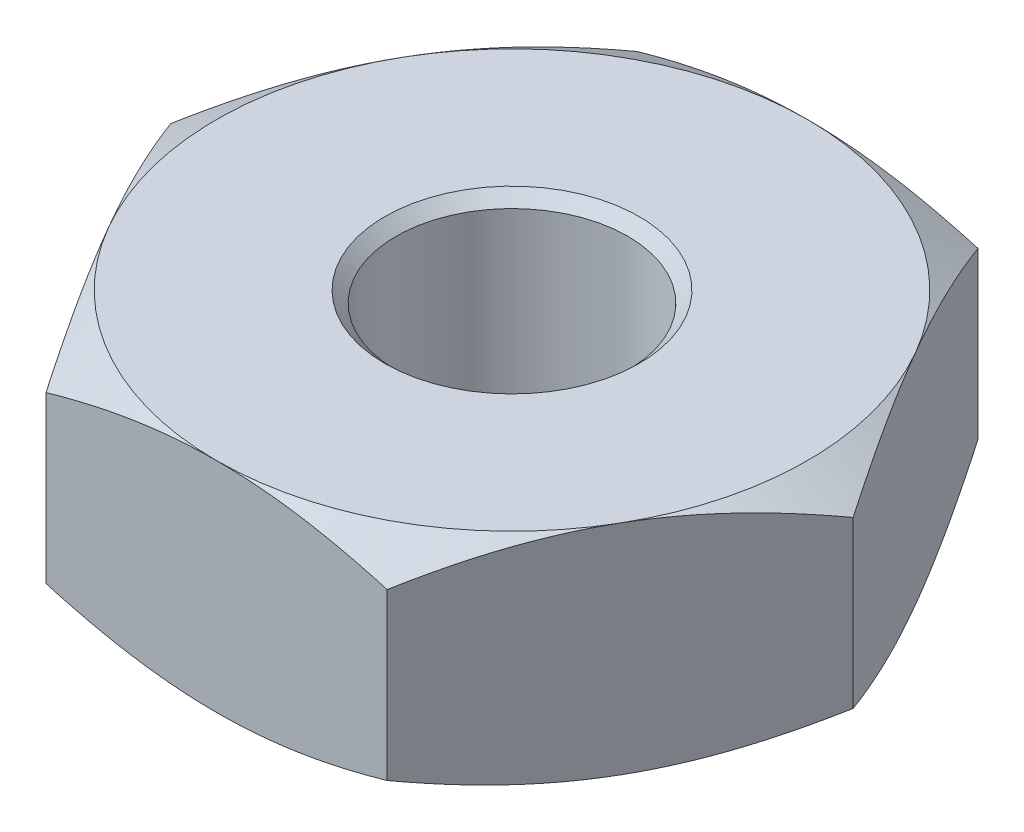
SolidWorks part; units mm, degrees
ref_plane "Front Plane" through (0, 0, 0) normal (0, 0, 1) x (1, 0, 0)
ref_plane "Top Plane" through (0, 0, 0) normal (0, 1, 0) x (1, 0, 0)
ref_plane "Right Plane" through (0, 0, 0) normal (1, 0, 0) x (0, 0, -1)
sketch "Sketch1" plane through (0, 0, 0) normal (0, 1, 0) x (1, 0, 0)
  line L1 (15.0111, 0) -> (7.5056, 13)
  line L2 (7.5056, 13) -> (-7.5056, 13)
  line L3 (-7.5056, 13) -> (-15.0111, 0)
  line L4 (-15.0111, 0) -> (-7.5056, -13)
  line L5 (-7.5056, -13) -> (7.5056, -13)
  line L6 (7.5056, -13) -> (15.0111, 0)
  circle A0 centre (0, 0) radius 13 construction
extrude "Boss-Extrude1" add sketch "Sketch1" along normal blind 9.6
sketch "Sketch2" plane through (0, 9.6, 0) normal (0, 1, 0) x (1, 0, 0)
  circle A0 centre (0, 0) radius 13
extrude "Cut-Extrude1" cut sketch "Sketch2" against normal blind 9.6 draft 60 flip side to cut
sketch "Sketch3" plane through (0, 0, 0) normal (0, -1, 0) x (1, 0, 0)
  circle A0 centre (0, 0) radius 13
extrude "Cut-Extrude2" cut sketch "Sketch3" against normal blind 9.6 draft 60 flip side to cut
hole_wizard "M12 Tapped Hole1" positions "Sketch4" profile "Sketch5" tap size "M12" standard "ISO"
sketch "Sketch4" plane through (0, 9.6, 0) normal (0, 1, 0) x (1, 0, 0)
  point P0 (0, 0)
sketch "Sketch5" plane through (0, 9.6, 0) normal (1, 0, 0) x (0, 0, 1)
  line L0 (0, 0) -> (0, 32.75)
  line L1 (0, 32.75) -> (5.1, 32.75)
  line L2 (5.1, 32.75) -> (5.1, 0)
  line L5 (5.1, 0) -> (0, 0)
  line L10 (0, 32.75) -> (-5.1, 32.75) construction
  line L11 (0, -6.35) -> (0, 107.95) construction
  dimension "Tap Drill Dia." = 10.2
  dimension "Tap Drill Depth" = 32.75
  dimension "Drill Angle" = 180
cosmetic thread "Hole Thread1" parameters "D1"=24, "D2"=12
chamfer "Chamfer1" distance 0.5 angle 45 2 edges at (0, 0, 5.1) (0, 9.6, 5.1)
